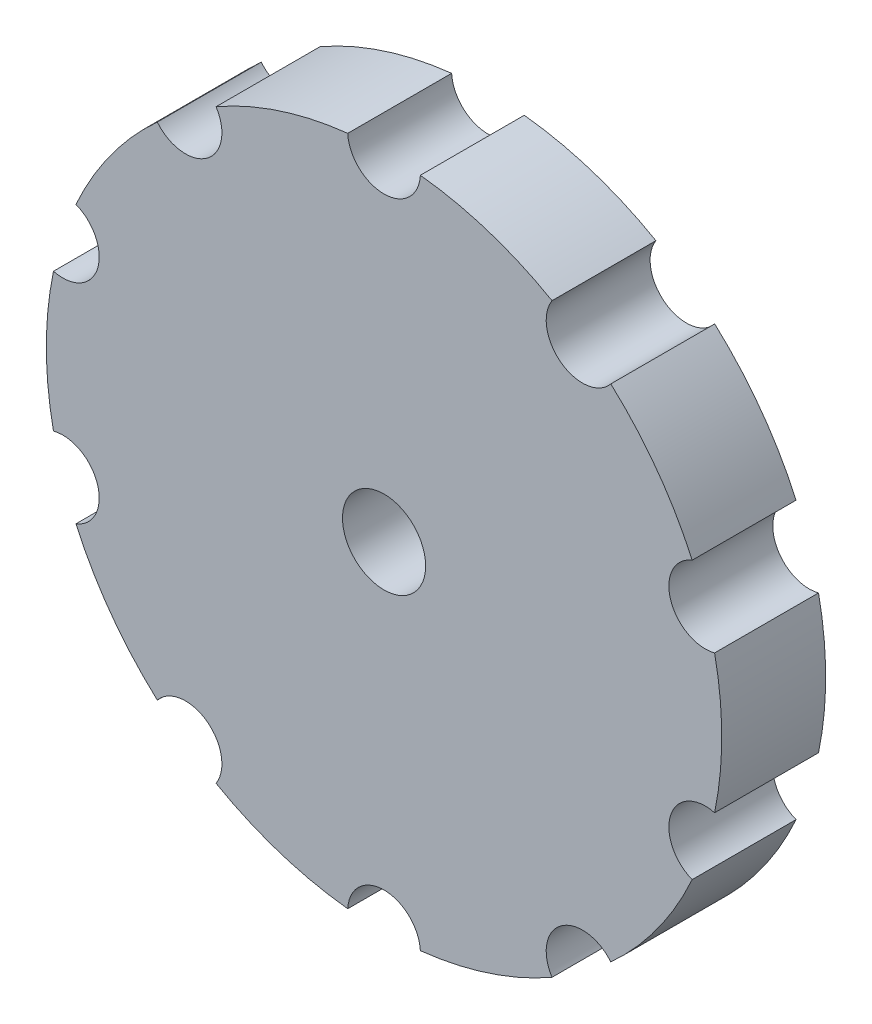
SolidWorks part; units mm, degrees
ref_plane "Alzado" through (0, 0, 0) normal (0, 0, 1) x (1, 0, 0)
ref_plane "Planta" through (0, 0, 0) normal (0, 1, 0) x (1, 0, 0)
ref_plane "Vista lateral" through (0, 0, 0) normal (1, 0, 0) x (0, 0, -1)
sketch "Croquis1" plane through (0, 0, 0) normal (0, 0, 1) x (1, 0, 0)
  arc A0 (-31.8101, 6.6609) -> (-31.8101, -6.6609) centre (0, 0) ccw
  circle A1 centre (0, 0) radius 4
  arc A2 (-3.4949, 32.3115) -> (3.4949, 32.3115) centre (0, 32.5) ccw
  arc A3 (-31.8101, 6.6609) -> (-31.8101, -6.6609) centre (0, 0) ccw
  arc A4 (16.1648, 28.1948) -> (21.8197, 24.0863) centre (19.103, 26.2931) ccw
  arc A5 (-31.8101, 6.6609) -> (-31.8101, -6.6609) centre (0, 0) ccw
  arc A6 (29.6501, 13.3087) -> (31.8101, 6.6609) centre (30.9093, 10.0431) ccw
  arc A7 (-31.8101, 6.6609) -> (-31.8101, -6.6609) centre (0, 0) ccw
  arc A8 (31.8101, -6.6609) -> (29.6501, -13.3087) centre (30.9093, -10.0431) ccw
  arc A9 (-31.8101, 6.6609) -> (-31.8101, -6.6609) centre (0, 0) ccw
  arc A10 (21.8197, -24.0863) -> (16.1648, -28.1948) centre (19.103, -26.2931) ccw
  arc A11 (-31.8101, 6.6609) -> (-31.8101, -6.6609) centre (0, 0) ccw
  arc A12 (3.4949, -32.3115) -> (-3.4949, -32.3115) centre (0, -32.5) ccw
  arc A13 (-31.8101, 6.6609) -> (-31.8101, -6.6609) centre (0, 0) ccw
  arc A14 (-16.1648, -28.1948) -> (-21.8197, -24.0863) centre (-19.103, -26.2931) ccw
  arc A15 (-31.8101, 6.6609) -> (-31.8101, -6.6609) centre (0, 0) ccw
  arc A16 (-29.6501, -13.3087) -> (-31.8101, -6.6609) centre (-30.9093, -10.0431) ccw
  arc A17 (-31.8101, 6.6609) -> (-31.8101, -6.6609) centre (0, 0) ccw
  arc A18 (-31.8101, 6.6609) -> (-29.6501, 13.3087) centre (-30.9093, 10.0431) ccw
  arc A19 (-31.8101, 6.6609) -> (-31.8101, -6.6609) centre (0, 0) ccw
  arc A20 (-21.8197, 24.0863) -> (-16.1648, 28.1948) centre (-19.103, 26.2931) ccw
  arc A21 (-21.8197, 24.0863) -> (-29.6501, 13.3087) centre (0, 0) ccw
  arc A22 (-21.8197, 24.0863) -> (-29.6501, 13.3087) centre (0, 0) ccw
  arc A23 (-21.8197, 24.0863) -> (-29.6501, 13.3087) centre (0, 0) ccw
  arc A24 (-21.8197, 24.0863) -> (-29.6501, 13.3087) centre (0, 0) ccw
  arc A25 (-21.8197, 24.0863) -> (-29.6501, 13.3087) centre (0, 0) ccw
  arc A26 (-21.8197, 24.0863) -> (-29.6501, 13.3087) centre (0, 0) ccw
  arc A27 (-21.8197, 24.0863) -> (-29.6501, 13.3087) centre (0, 0) ccw
  arc A28 (-21.8197, 24.0863) -> (-29.6501, 13.3087) centre (0, 0) ccw
  arc A29 (-21.8197, 24.0863) -> (-29.6501, 13.3087) centre (0, 0) ccw
  arc A30 (-21.8197, 24.0863) -> (-29.6501, 13.3087) centre (0, 0) ccw
  arc A31 (-3.4949, 32.3115) -> (-16.1648, 28.1948) centre (0, 0) ccw
  arc A32 (-3.4949, 32.3115) -> (-16.1648, 28.1948) centre (0, 0) ccw
  arc A33 (-3.4949, 32.3115) -> (-16.1648, 28.1948) centre (0, 0) ccw
  arc A34 (-3.4949, 32.3115) -> (-16.1648, 28.1948) centre (0, 0) ccw
  arc A35 (-3.4949, 32.3115) -> (-16.1648, 28.1948) centre (0, 0) ccw
  arc A36 (-3.4949, 32.3115) -> (-16.1648, 28.1948) centre (0, 0) ccw
  arc A37 (-3.4949, 32.3115) -> (-16.1648, 28.1948) centre (0, 0) ccw
  arc A38 (-3.4949, 32.3115) -> (-16.1648, 28.1948) centre (0, 0) ccw
  arc A39 (-3.4949, 32.3115) -> (-16.1648, 28.1948) centre (0, 0) ccw
  arc A40 (-3.4949, 32.3115) -> (-16.1648, 28.1948) centre (0, 0) ccw
  arc A41 (16.1648, 28.1948) -> (3.4949, 32.3115) centre (0, 0) ccw
  arc A42 (16.1648, 28.1948) -> (3.4949, 32.3115) centre (0, 0) ccw
  arc A43 (16.1648, 28.1948) -> (3.4949, 32.3115) centre (0, 0) ccw
  arc A44 (16.1648, 28.1948) -> (3.4949, 32.3115) centre (0, 0) ccw
  arc A45 (16.1648, 28.1948) -> (3.4949, 32.3115) centre (0, 0) ccw
  arc A46 (16.1648, 28.1948) -> (3.4949, 32.3115) centre (0, 0) ccw
  arc A47 (16.1648, 28.1948) -> (3.4949, 32.3115) centre (0, 0) ccw
  arc A48 (16.1648, 28.1948) -> (3.4949, 32.3115) centre (0, 0) ccw
  arc A49 (16.1648, 28.1948) -> (3.4949, 32.3115) centre (0, 0) ccw
  arc A50 (16.1648, 28.1948) -> (3.4949, 32.3115) centre (0, 0) ccw
  arc A51 (29.6501, 13.3087) -> (21.8197, 24.0863) centre (0, 0) ccw
  arc A52 (29.6501, 13.3087) -> (21.8197, 24.0863) centre (0, 0) ccw
  arc A53 (29.6501, 13.3087) -> (21.8197, 24.0863) centre (0, 0) ccw
  arc A54 (29.6501, 13.3087) -> (21.8197, 24.0863) centre (0, 0) ccw
  arc A55 (29.6501, 13.3087) -> (21.8197, 24.0863) centre (0, 0) ccw
  arc A56 (29.6501, 13.3087) -> (21.8197, 24.0863) centre (0, 0) ccw
  arc A57 (29.6501, 13.3087) -> (21.8197, 24.0863) centre (0, 0) ccw
  arc A58 (29.6501, 13.3087) -> (21.8197, 24.0863) centre (0, 0) ccw
  arc A59 (29.6501, 13.3087) -> (21.8197, 24.0863) centre (0, 0) ccw
  arc A60 (29.6501, 13.3087) -> (21.8197, 24.0863) centre (0, 0) ccw
  arc A61 (31.8101, -6.6609) -> (31.8101, 6.6609) centre (0, 0) ccw
  arc A62 (31.8101, -6.6609) -> (31.8101, 6.6609) centre (0, 0) ccw
  arc A63 (31.8101, -6.6609) -> (31.8101, 6.6609) centre (0, 0) ccw
  arc A64 (31.8101, -6.6609) -> (31.8101, 6.6609) centre (0, 0) ccw
  arc A65 (31.8101, -6.6609) -> (31.8101, 6.6609) centre (0, 0) ccw
  arc A66 (31.8101, -6.6609) -> (31.8101, 6.6609) centre (0, 0) ccw
  arc A67 (31.8101, -6.6609) -> (31.8101, 6.6609) centre (0, 0) ccw
  arc A68 (31.8101, -6.6609) -> (31.8101, 6.6609) centre (0, 0) ccw
  arc A69 (31.8101, -6.6609) -> (31.8101, 6.6609) centre (0, 0) ccw
  arc A70 (31.8101, -6.6609) -> (31.8101, 6.6609) centre (0, 0) ccw
  arc A71 (21.8197, -24.0863) -> (29.6501, -13.3087) centre (0, 0) ccw
  arc A72 (21.8197, -24.0863) -> (29.6501, -13.3087) centre (0, 0) ccw
  arc A73 (21.8197, -24.0863) -> (29.6501, -13.3087) centre (0, 0) ccw
  arc A74 (21.8197, -24.0863) -> (29.6501, -13.3087) centre (0, 0) ccw
  arc A75 (21.8197, -24.0863) -> (29.6501, -13.3087) centre (0, 0) ccw
  arc A76 (21.8197, -24.0863) -> (29.6501, -13.3087) centre (0, 0) ccw
  arc A77 (21.8197, -24.0863) -> (29.6501, -13.3087) centre (0, 0) ccw
  arc A78 (21.8197, -24.0863) -> (29.6501, -13.3087) centre (0, 0) ccw
  arc A79 (21.8197, -24.0863) -> (29.6501, -13.3087) centre (0, 0) ccw
  arc A80 (21.8197, -24.0863) -> (29.6501, -13.3087) centre (0, 0) ccw
  arc A81 (3.4949, -32.3115) -> (16.1648, -28.1948) centre (0, 0) ccw
  arc A82 (3.4949, -32.3115) -> (16.1648, -28.1948) centre (0, 0) ccw
  arc A83 (3.4949, -32.3115) -> (16.1648, -28.1948) centre (0, 0) ccw
  arc A84 (3.4949, -32.3115) -> (16.1648, -28.1948) centre (0, 0) ccw
  arc A85 (3.4949, -32.3115) -> (16.1648, -28.1948) centre (0, 0) ccw
  arc A86 (3.4949, -32.3115) -> (16.1648, -28.1948) centre (0, 0) ccw
  arc A87 (3.4949, -32.3115) -> (16.1648, -28.1948) centre (0, 0) ccw
  arc A88 (3.4949, -32.3115) -> (16.1648, -28.1948) centre (0, 0) ccw
  arc A89 (3.4949, -32.3115) -> (16.1648, -28.1948) centre (0, 0) ccw
  arc A90 (3.4949, -32.3115) -> (16.1648, -28.1948) centre (0, 0) ccw
  arc A91 (-16.1648, -28.1948) -> (-3.4949, -32.3115) centre (0, 0) ccw
  arc A92 (-16.1648, -28.1948) -> (-3.4949, -32.3115) centre (0, 0) ccw
  arc A93 (-16.1648, -28.1948) -> (-3.4949, -32.3115) centre (0, 0) ccw
  arc A94 (-16.1648, -28.1948) -> (-3.4949, -32.3115) centre (0, 0) ccw
  arc A95 (-16.1648, -28.1948) -> (-3.4949, -32.3115) centre (0, 0) ccw
  arc A96 (-16.1648, -28.1948) -> (-3.4949, -32.3115) centre (0, 0) ccw
  arc A97 (-16.1648, -28.1948) -> (-3.4949, -32.3115) centre (0, 0) ccw
  arc A98 (-16.1648, -28.1948) -> (-3.4949, -32.3115) centre (0, 0) ccw
  arc A99 (-16.1648, -28.1948) -> (-3.4949, -32.3115) centre (0, 0) ccw
  arc A100 (-16.1648, -28.1948) -> (-3.4949, -32.3115) centre (0, 0) ccw
  arc A101 (-29.6501, -13.3087) -> (-21.8197, -24.0863) centre (0, 0) ccw
  arc A102 (-29.6501, -13.3087) -> (-21.8197, -24.0863) centre (0, 0) ccw
  arc A103 (-29.6501, -13.3087) -> (-21.8197, -24.0863) centre (0, 0) ccw
  arc A104 (-29.6501, -13.3087) -> (-21.8197, -24.0863) centre (0, 0) ccw
  arc A105 (-29.6501, -13.3087) -> (-21.8197, -24.0863) centre (0, 0) ccw
  arc A106 (-29.6501, -13.3087) -> (-21.8197, -24.0863) centre (0, 0) ccw
  arc A107 (-29.6501, -13.3087) -> (-21.8197, -24.0863) centre (0, 0) ccw
  arc A108 (-29.6501, -13.3087) -> (-21.8197, -24.0863) centre (0, 0) ccw
  arc A109 (-29.6501, -13.3087) -> (-21.8197, -24.0863) centre (0, 0) ccw
  arc A110 (-29.6501, -13.3087) -> (-21.8197, -24.0863) centre (0, 0) ccw
  point P36 (0, 0)
  dimension "D1" = 8
  dimension "D2" = 65
  dimension "D3" = 7
  dimension "D4" = 10
extrude "Saliente-Extruir1" add sketch "Croquis1" along normal blind 10 contours A16 A101 A14 A91 A12 A81 A10 A71 A8 A61 A6 A51 A4 A41 A2 A31 A20 A21 A18 A0 A1
